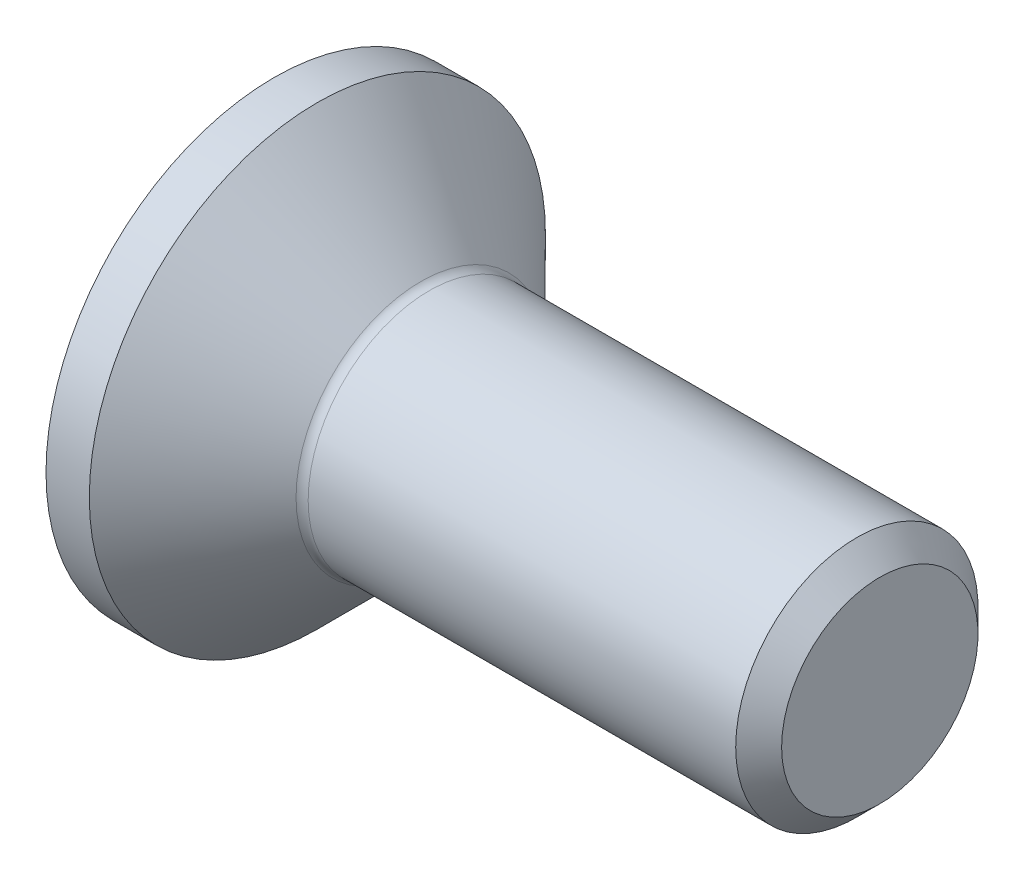
SolidWorks part; units mm, degrees
ref_plane "Front" through (0, 0, 0) normal (0, 0, 1) x (1, 0, 0)
ref_plane "Top" through (0, 0, 0) normal (0, 1, 0) x (1, 0, 0)
ref_plane "Right" through (0, 0, 0) normal (1, 0, 0) x (0, 0, -1)
sketch "Sketch1" plane through (0, 0, 0) normal (0, 0, 1) x (1, 0, 0)
  line L0 (0, 0) -> (0, 4.48)
  line L1 (0, 4.48) -> (2.48, 2)
  line L2 (2.48, 2) -> (10, 2)
  line L3 (10, 2) -> (10, 0)
  line L4 (10, 0) -> (0, 0)
  line L5 (-0.5871, 0) -> (5.4927, 0) construction
  dimension "D1" = 45
  dimension "l" = 10
  dimension "k" = 2.48
  dimension "d" = 4
revolve "Base" add sketch "Sketch1" angle 360 about L5
cosmetic thread "ThreadCosmetic1" [suppressed] parameters "b"=7.5, "D2"=3.242
sketch "Sketch2" plane through (0, 0, 0) normal (1, 0, 0) x (0, 0, -1)
  line L1 (1.4434, 0) -> (0.7217, 1.25)
  line L2 (0.7217, 1.25) -> (-0.7217, 1.25)
  line L3 (-0.7217, 1.25) -> (-1.4434, 0)
  line L4 (-1.4434, 0) -> (-0.7217, -1.25)
  line L5 (-0.7217, -1.25) -> (0.7217, -1.25)
  line L6 (0.7217, -1.25) -> (1.4434, 0)
  circle A0 centre (0, 0) radius 1.25 construction
  dimension "s" = 2.5
extrude "HexagonSocket" cut sketch "Sketch2" along normal blind 1.5
sketch "Sketch3" plane through (0, 0, 0) normal (0, 0, 1) x (1, 0, 0)
  line L0 (-0.4391, 0) -> (4.425, 0) construction
  line L1 (1.5, 0) -> (1.5, -1.25) construction
  line L2 (1.5, 1.25) -> (2.2217, 0)
  line L3 (2.2217, 0) -> (1.5, -1.25) construction
  line L4 (1.5, 1.25) -> (1.5, 0)
  line L5 (1.5, 0) -> (2.2217, 0)
  line L7 (1.5, 1.25) -> (1.5, 0) construction
  dimension "D1" = 120
revolve "Cut-Revolve1" cut sketch "Sketch3" angle 360 about L0
fillet "HeadFillet" radius 0.2 1 edges at (2.48, 0, 2)
chamfer "Chamfer" distance 0.379 angle 45 1 edges at (10, 0, 2)
sketch "Sketch4" plane through (0, 0, 0) normal (0, 1, 0) x (1, 0, 0)
  line L0 (11.8531, 0) -> (-2.694, 0) construction
  line L1 (-2, 8.765) -> (3, 8.765)
  line L2 (-2, 8.765) -> (-2, 3.765)
  line L3 (-2, 3.765) -> (3, 3.765)
  line L4 (3, 8.765) -> (3, 3.765)
  line L5 (0, 4.48) -> (0, -4.48) construction
  dimension "dk" = 7.53
  dimension "D2" = 2
  dimension "D3" = 5
  dimension "D4" = 5
revolve "Cut-Revolve2" cut sketch "Sketch4" angle 360 about L0
sketch "Sketch5" plane through (0, 0, 0) normal (0, 0, 1) x (1, 0, 0)
  line L0 (9.621, 1.6718) -> (9.8105, 2)
  line L1 (9.8105, 2) -> (9.8105, 2.379)
  line L2 (9.8105, 2.379) -> (9.4315, 2.379)
  line L3 (9.4315, 2.379) -> (9.4315, 2)
  line L4 (9.4315, 2) -> (9.621, 1.6718)
  line L5 (0, 0) -> (10.6885, 0) construction
  line L6 (9.621, 2) -> (9.621, -2) construction
  dimension "D1" = 4
  dimension "D2" = 0.379
revolve "Cut-Revolve10" [suppressed] cut sketch "Sketch5" angle 360 about L5
pattern_linear "LPattern10" [suppressed] count 16 spacing 0.4548 along (1, 0, 0)
equation "\"D1@Chamfer\" = (  \"d@Sketch1\" - \"D2@ThreadCosmetic1\" )  / 2"
equation "\"D1@Sketch5\" = \"d@Sketch1\""
equation "\"D2@Sketch5\" =  ( \"d@Sketch1\" - \"D2@ThreadCosmetic1\" )  / 2"
equation "\"D3@LPattern10\" = \"D2@Sketch5\" * 1.2"
equation "\"D1@LPattern10\" = \"b@ThreadCosmetic1\" / \"D3@LPattern10\""
